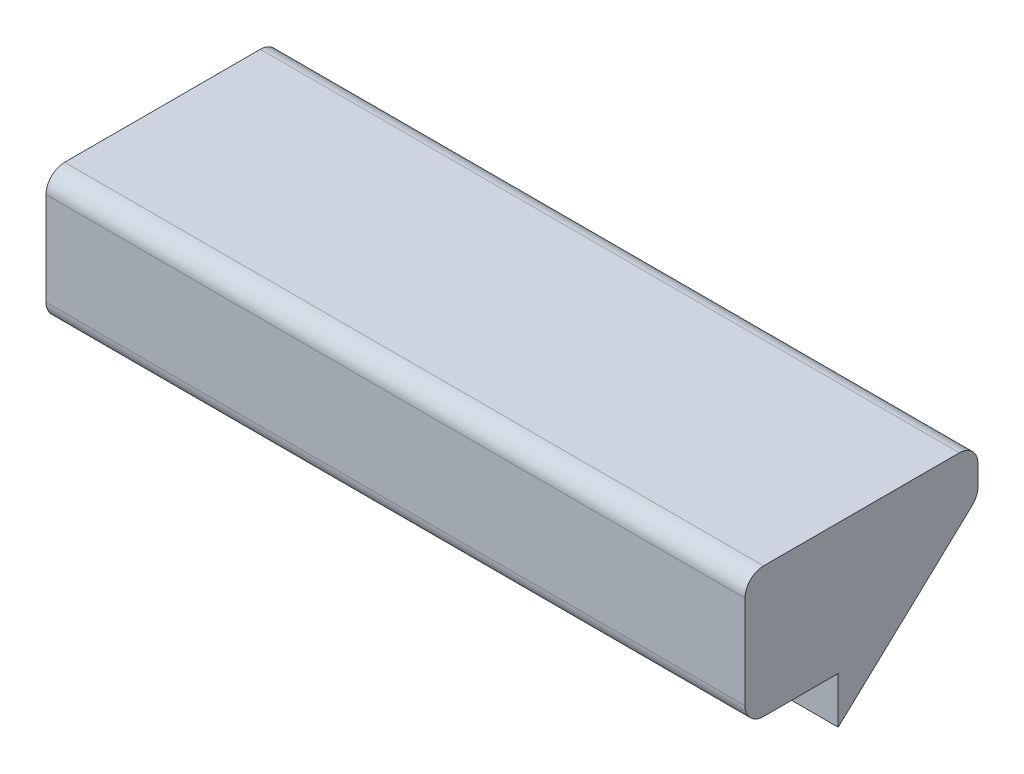
SolidWorks part; units mm, degrees
material "3DP"
ref_plane "正面" through (0, 0, 0) normal (0, 0, 1) x (1, 0, 0)
ref_plane "平面" through (0, 0, 0) normal (0, 1, 0) x (1, 0, 0)
ref_plane "右側面" through (0, 0, 0) normal (1, 0, 0) x (0, 0, -1)
sketch "ｽｹｯﾁ1" plane through (0, 0, 0) normal (1, 0, 0) x (0, 0, -1)
  line L0 (0, 0) -> (0, -14)
  line L1 (0, -14) -> (10, -14)
  line L2 (10, -14) -> (10, -19)
  line L3 (10, -19) -> (25, -5)
  line L4 (25, -5) -> (25, 0)
  line L5 (25, 0) -> (0, 0)
  dimension "D1" = 10
  dimension "D2" = 14
  dimension "D3" = 25
  dimension "D4" = 5
  dimension "D5" = 5
extrude "ﾎﾞｽ - 押し出し1" add sketch "ｽｹｯﾁ1" along normal blind 75
fillet "ﾌｨﾚｯﾄ1" radius 2 4 edges at (37.5, 0, 0) (37.5, -14, 0) (37.5, -5, -25) (37.5, 0, -25)
